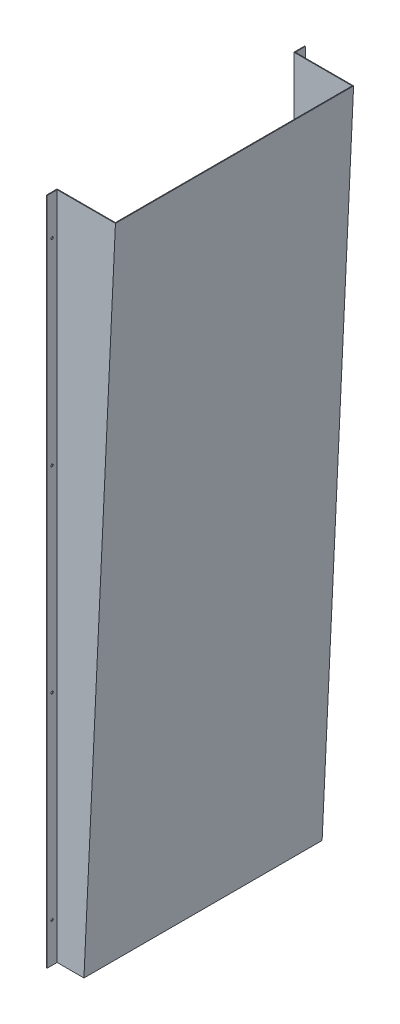
SolidWorks part; units mm, degrees
ref_plane "Front Plane" through (0, 0, 0) normal (0, 0, 1) x (1, 0, 0)
ref_plane "Top Plane" through (0, 0, 0) normal (0, 1, 0) x (1, 0, 0)
ref_plane "Right Plane" through (0, 0, 0) normal (1, 0, 0) x (0, 0, -1)
sketch "Sketch1" plane through (0, 0, 0) normal (1, 0, 0) x (0, 0, -1)
  line L1 (-302.5, -850) -> (302.5, -850)
  line L2 (-302.5, -850) -> (-302.5, 850)
  line L3 (-302.5, 850) -> (302.5, 850)
  line L4 (302.5, -850) -> (302.5, 850)
  line L5 (-302.5, -850) -> (302.5, 850) construction
  line L6 (-302.5, 850) -> (302.5, -850) construction
  point P0 (0, 0)
  dimension "D1" = 1700
  dimension "D2" = 605
sketch "Sketch21" plane through (0, 0, 0) normal (0, 0, 1) x (1, 0, 0)
  line L0 (-75, -850) -> (-75, 850)
  line L1 (-75, 850) -> (75, 850)
  line L2 (75, 850) -> (-5, -850)
  line L3 (-5, -850) -> (-75, -850)
  point P2 (0, 850)
  point P5 (-75, 0)
  dimension "D1" = 1700
  dimension "D2" = 150
  dimension "D3" = 70
extrude "Boss-Extrude1" add sketch "Sketch21" along normal mid plane 605
shell "Shell1" thickness 1.8
sketch "Sketch22" plane through (0, 850, 0) normal (0, 1, 0) x (1, 0, 0)
  line L4 (73.1133, 300.7) -> (-75, 300.7)
  line L5 (73.1133, -300.7) -> (73.1133, 300.7)
  line L6 (-75, -300.7) -> (73.1133, -300.7)
  line L7 (-75, 300.7) -> (-75, -300.7)
  line L8 (73.1133, 300.7) -> (-75, 300.7)
  line L9 (73.1133, -300.7) -> (73.1133, 300.7)
  line L10 (-75, -300.7) -> (73.1133, -300.7)
  line L11 (-75, 300.7) -> (-75, -300.7)
  dimension "D1" = 0
extrude "Cut-Extrude4" cut sketch "Sketch22" against normal up to next
sketch "Sketch23" plane through (0, -848.2, 0) normal (0, 1, 0) x (1, 0, 0)
  line L4 (-6.7173, 300.7) -> (-75, 300.7)
  line L5 (-75, 300.7) -> (-75, -300.7)
  line L6 (-75, -300.7) -> (-6.7173, -300.7)
  line L7 (-6.7173, -300.7) -> (-6.7173, 300.7)
  line L8 (-6.7173, 300.7) -> (-75, 300.7)
  line L9 (-75, 300.7) -> (-75, -300.7)
  line L10 (-75, -300.7) -> (-6.7173, -300.7)
  line L11 (-6.7173, -300.7) -> (-6.7173, 300.7)
  dimension "D1" = 0
extrude "Cut-Extrude5" cut sketch "Sketch23" against normal up to next
sketch "Sketch24" plane through (-75, 0, 0) normal (-1, 0, 0) x (0, 0, 1)
  line L0 (-300.7, -850) -> (-302.5, -850) construction
  line L1 (-302.5, 850) -> (-327.9, 850)
  line L2 (-302.5, 850) -> (-302.5, -850)
  line L3 (-302.5, -850) -> (-327.9, -850)
  line L4 (-327.9, 850) -> (-327.9, -850)
  line L5 (0, 0) -> (0, -321.9642) construction
  line L6 (327.9, 850) -> (327.9, -850)
  line L7 (302.5, -850) -> (327.9, -850)
  line L8 (302.5, 850) -> (302.5, -850)
  line L9 (302.5, 850) -> (327.9, 850)
  dimension "D1" = 25.4
extrude "Boss-Extrude2" add sketch "Sketch24" against normal blind 1.8
sketch "Sketch25" plane through (-73.2, 0, 0) normal (1, 0, 0) x (0, 0, -1)
  line L0 (-327.9, 850) -> (-302.5, 850) construction
  circle A0 centre (-315.2, 750) radius 3
  circle A1 centre (-315.2, 250) radius 3
  circle A2 centre (-315.2, -250) radius 3
  circle A3 centre (-315.2, -750) radius 3
  point P4 (-315.2, 850)
  point P5 (0, 0)
  dimension "D2" = 6
  dimension "D4" = 500
  dimension "D1" = 100
  dimension "D3" = 4
extrude "Cut-Extrude6" cut sketch "Sketch25" against normal blind 10
mirror "Mirror1" about plane through (0, 0, 0) normal (0, 0, 1) of "Cut-Extrude6"
